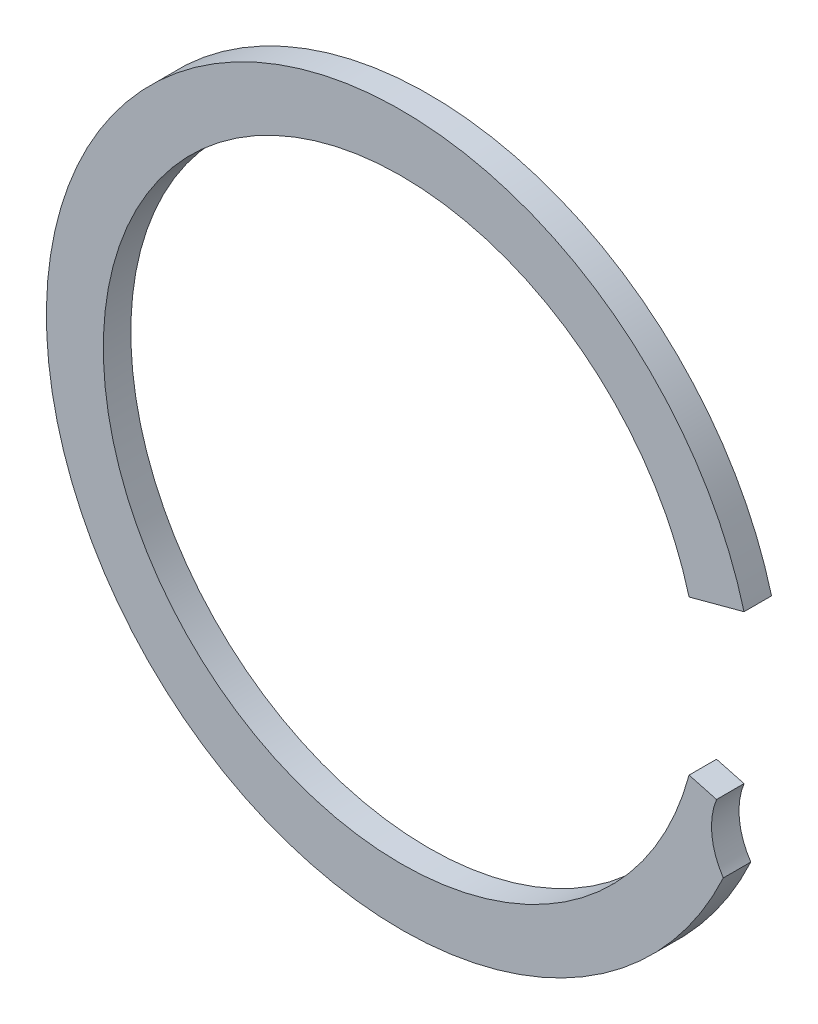
SolidWorks part; units mm, degrees
material "Steel Spring  ASTM A228 "
ref_plane "Front Plane" through (0, 0, 0) normal (0, 0, 1) x (1, 0, 0)
ref_plane "Top Plane" through (0, 0, 0) normal (0, 1, 0) x (1, 0, 0)
ref_plane "Right Plane" through (0, 0, 0) normal (1, 0, 0) x (0, 0, -1)
ref_plane "Plane4" through (0, 0, 0) normal (0, 0, -1) x (-1, 0, 0)
sketch "Sketch1" plane through (0, 0, 0) normal (0, 0, -1) x (-1, 0, 0)
  line L0 (-14.3343, 3.8409) -> (-12.0354, 3.2249)
  line L1 (-12.0354, -3.2249) -> (-13.1849, -3.5329)
  arc A0 (-13.4673, -6.2335) -> (-14.3343, 3.8409) centre (0, 0) ccw
  arc A1 (-12.0354, 3.2249) -> (-12.0354, -3.2249) centre (0, 0) cw
  arc A2 (-13.1849, -3.5329) -> (-13.4673, -6.2335) centre (-15.8561, -4.6186) cw
extrude "Boss-Extrude1" add sketch "Sketch1" against normal blind 1.15
